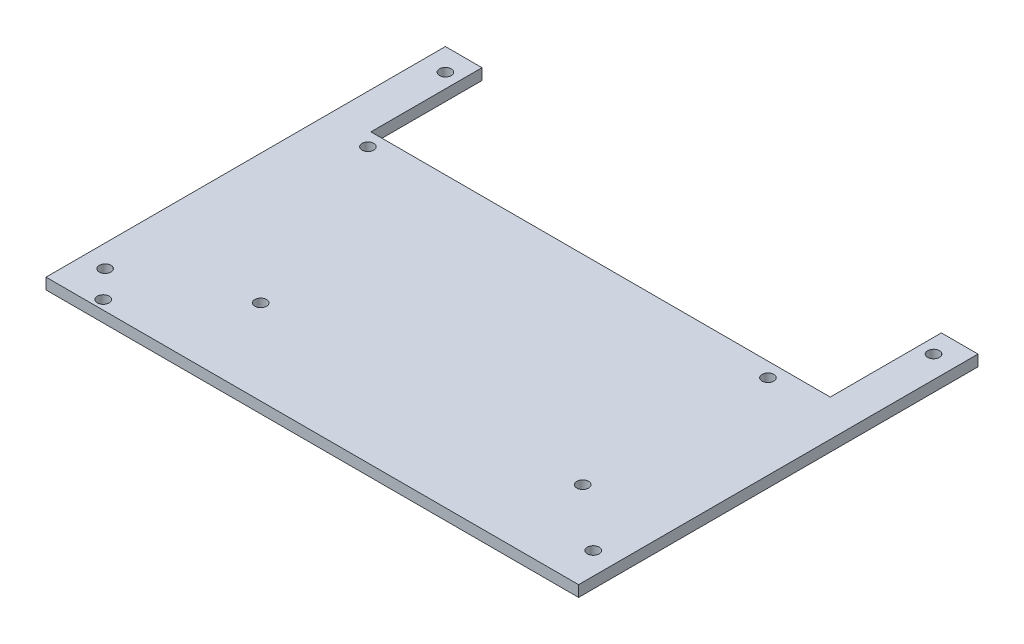
SolidWorks part; units mm, degrees
ref_plane "Front Plane" through (0, 0, 0) normal (0, 0, 1) x (1, 0, 0)
ref_plane "Top Plane" through (0, 0, 0) normal (0, 1, 0) x (1, 0, 0)
ref_plane "Right Plane" through (0, 0, 0) normal (1, 0, 0) x (0, 0, -1)
sketch "Sketch1" plane through (0, 0, 0) normal (0, 1, 0) x (1, 0, 0)
  line L0 (-6, 97.8583) -> (137.7752, 97.8583)
  line L1 (0, 0) -> (131.7752, 0) construction
  line L2 (0, 0) -> (0, 91.8583) construction
  line L3 (0, 91.8583) -> (131.7752, 91.8583) construction
  line L4 (131.7752, 0) -> (131.7752, 91.8583) construction
  line L5 (137.7752, -6) -> (137.7752, 97.8583)
  line L6 (-6, -6) -> (137.7752, -6) construction
  line L7 (-6, -6) -> (-6, 97.8583)
  line L8 (0, -9.96) -> (131.7752, -9.96)
  line L9 (-6, -6) -> (-6, -9.96)
  line L10 (-6, -9.96) -> (0, -9.96)
  line L11 (131.7752, -9.96) -> (137.7752, -9.96)
  line L12 (137.7752, -9.96) -> (137.7752, -6)
  circle A0 centre (0, 91.8583) radius 1.59
  circle A1 centre (131.7752, 91.8583) radius 1.59
  circle A2 centre (131.7752, 0) radius 1.59
  circle A3 centre (0, 0) radius 1.59
  dimension "D1" = 6
  dimension "D2" = 9.96
extrude "Extrude1" add sketch "Sketch1" against normal blind 3
sketch "Sketch2" plane through (0, 0, 0) normal (0, 1, 0) x (1, 0, 0)
  line L0 (65.8876, 97.8583) -> (65.8876, -9.96) construction
  line L1 (137.7752, 97.8583) -> (-6, 97.8583) construction
  line L2 (-6, -9.96) -> (137.7752, -9.96) construction
  line L3 (3.8876, 97.8583) -> (127.8876, 97.8583)
  line L4 (127.8876, 97.8583) -> (127.8876, 67.8583)
  line L5 (127.8876, 67.8583) -> (3.8876, 67.8583)
  line L6 (3.8876, 97.8583) -> (3.8876, 67.8583)
  line L7 (-6, 43.9492) -> (137.7752, 43.9492) construction
  line L8 (-6, 97.8583) -> (-6, -9.96) construction
  line L9 (137.7752, -9.96) -> (137.7752, 97.8583) construction
  point P11 (65.8876, 67.8583)
extrude "Extrude2" cut sketch "Sketch2" against normal up to surface (3 mm away) up to face at (0, -3, 1.59)
sketch "Sketch3" plane through (0, 0, 0) normal (0, 1, 0) x (1, 0, 0)
  line L0 (0, 0) -> (0, 13) construction
  line L1 (0, 13) -> (29, 13) construction
  circle A0 centre (6.9613, -7.4688) radius 1.59
  circle A1 centre (6.9705, 63.9702) radius 1.59
  circle A2 centre (114.9705, 63.9563) radius 1.59
  circle A3 centre (114.964, 13.9563) radius 1.59
  circle A4 centre (29, 13) radius 1.59
extrude "Extrude3" cut sketch "Sketch3" against normal up to surface (3 mm away) up to face at (65.8876, -3, -63.4037)
